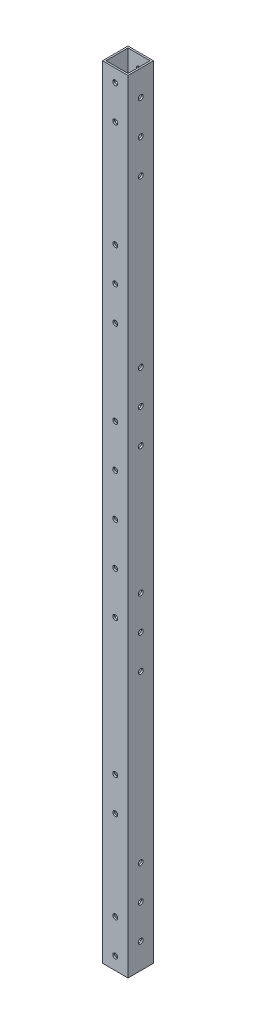
SolidWorks part; units mm, degrees
material "Thornel Mat VMA"
ref_plane "前视基准面" through (0, 0, 0) normal (0, 0, 1) x (1, 0, 0)
ref_plane "上视基准面" through (0, 0, 0) normal (0, 1, 0) x (1, 0, 0)
ref_plane "右视基准面" through (0, 0, 0) normal (1, 0, 0) x (0, 0, -1)
sketch "草图1" plane through (0, 0, 0) normal (0, 1, 0) x (1, 0, 0)
  line L1 (-7.5, -7.5) -> (7.5, -7.5)
  line L2 (-7.5, -7.5) -> (-7.5, 7.5)
  line L3 (-7.5, 7.5) -> (7.5, 7.5)
  line L4 (7.5, -7.5) -> (7.5, 7.5)
  line L5 (-7.5, -7.5) -> (7.5, 7.5) construction
  line L6 (-7.5, 7.5) -> (7.5, -7.5) construction
  point P0 (0, 0)
  dimension "D1" = 15
  dimension "D2" = 15
extrude "拉伸-薄壁1" add sketch "草图1" along normal blind 460 thin thin type one direction reverse wall 1
sketch "草图2" plane through (0, 0, 7.5) normal (0, 0, 1) x (1, 0, 0)
  line L0 (0, 0) -> (0, 460) construction
  line L1 (-7.5, 460) -> (7.5, 460) construction
  line L2 (-1000, 230) -> (49000, 230) construction
  line L3 (-7.5, 0) -> (7.5, 0) construction
  circle A0 centre (0, 7.5) radius 1.45
  circle A1 centre (0, 27.5) radius 1.45
  circle A2 centre (0, 432.5) radius 1.45
  circle A3 centre (0, 452.5) radius 1.45
  circle A4 centre (0, 80) radius 1.45
  circle A5 centre (0, 100) radius 1.45
  circle A6 centre (0, 350) radius 1.45
  circle A7 centre (0, 370) radius 1.45
  circle A8 centre (0, 330) radius 1.45
  circle A9 centre (0, 230) radius 1.45
  circle A10 centre (0, 255) radius 1.45
  circle A11 centre (0, 280) radius 1.45
  circle A12 centre (0, 205) radius 1.45
  circle A13 centre (0, 180) radius 1.45
  point P8 (0, 230)
  dimension "D1" = 2.9
  dimension "D6" = 20
  dimension "D7" = 20
  dimension "D8" = 120
  dimension "D11" = 25
  dimension "D12" = 25
  dimension "D2" = 7.5
  dimension "D3" = 20
  dimension "D4" = 20
  dimension "D5" = 80
  dimension "D9" = 3
  dimension "D10" = 3
extrude "切除-拉伸1" cut sketch "草图2" against normal through all
sketch "草图3" plane through (7.5, 0, 0) normal (1, 0, 0) x (0, 0, -1)
  line L0 (0, 0) -> (0, 460) construction
  line L1 (-7.5, 460) -> (7.5, 460) construction
  line L2 (-1000, 230) -> (49000, 230) construction
  line L3 (-7.5, 0) -> (7.5, 0) construction
  circle A0 centre (0, 15) radius 1.45
  circle A1 centre (0, 35) radius 1.45
  circle A2 centre (0, 425) radius 1.45
  circle A3 centre (0, 445) radius 1.45
  circle A4 centre (0, 172.5) radius 1.45
  circle A5 centre (0, 192.5) radius 1.45
  circle A6 centre (0, 152.5) radius 1.45
  circle A7 centre (0, 307.5) radius 1.45
  circle A8 centre (0, 267.5) radius 1.45
  circle A9 centre (0, 287.5) radius 1.45
  circle A10 centre (0, 55) radius 1.45
  circle A11 centre (0, 405) radius 1.45
  point P12 (0, 230)
  dimension "D3" = 2.9
  dimension "D4" = 2.9
  dimension "D6" = 20
  dimension "D8" = 20
  dimension "D1" = 15
  dimension "D2" = 20
  dimension "D5" = 20
  dimension "D7" = 115
extrude "切除-拉伸2" cut sketch "草图3" against normal through all
